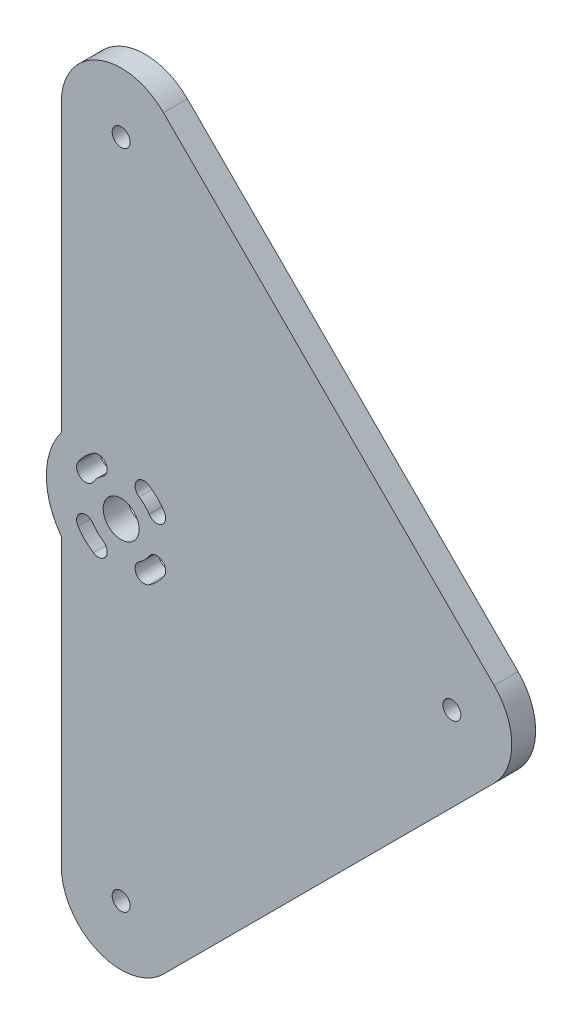
SolidWorks part; units mm, degrees
ref_plane "前视基准面" through (0, 0, 0) normal (0, 0, 1) x (1, 0, 0)
ref_plane "上视基准面" through (0, 0, 0) normal (0, 1, 0) x (1, 0, 0)
ref_plane "右视基准面" through (0, 0, 0) normal (1, 0, 0) x (0, 0, -1)
sketch "草图1" plane through (0, 0, 0) normal (0, 0, 1) x (1, 0, 0)
  line L0 (1790.7974, 1613.2668) -> (1790.7974, 1565.512)
  line L1 (1790.7974, 1550.512) -> (1790.7974, 1502.7572)
  line L2 (1807.8684, 1620.3379) -> (1863.1233, 1565.0831)
  line L3 (1863.1233, 1550.9409) -> (1807.8684, 1495.6861)
  circle A0 centre (1800.7974, 1558.012) radius 3
  circle A1 centre (1800.7974, 1613.2668) radius 1.5
  circle A2 centre (1856.0522, 1558.012) radius 1.5
  circle A3 centre (1800.7974, 1502.7572) radius 1.5
  arc A4 (1790.7974, 1502.7572) -> (1807.8684, 1495.6861) centre (1800.7974, 1502.7572) ccw
  arc A5 (1807.8684, 1620.3379) -> (1790.7974, 1613.2668) centre (1800.7974, 1613.2668) ccw
  arc A6 (1863.1233, 1550.9409) -> (1863.1233, 1565.0831) centre (1856.0522, 1558.012) ccw
  arc A7 (1790.7974, 1565.512) -> (1790.7974, 1550.512) centre (1800.7974, 1558.012) ccw
  arc A8 (1805.4433, 1550.8093) -> (1808.0001, 1553.3661) centre (1800.7974, 1558.012) ccw
  arc A9 (1808.0001, 1562.6579) -> (1805.4433, 1565.2147) centre (1800.7974, 1558.012) ccw
  arc A10 (1796.1515, 1565.2147) -> (1793.5947, 1562.6579) centre (1800.7974, 1558.012) ccw
  arc A11 (1793.5947, 1553.3661) -> (1796.1515, 1550.8093) centre (1800.7974, 1558.012) ccw
  arc A12 (1803.8171, 1553.3304) -> (1805.479, 1554.9923) centre (1800.7974, 1558.012) ccw
  arc A13 (1805.479, 1561.0318) -> (1803.8171, 1562.6937) centre (1800.7974, 1558.012) ccw
  arc A14 (1797.7776, 1562.6937) -> (1796.1157, 1561.0318) centre (1800.7974, 1558.012) ccw
  arc A15 (1796.1157, 1554.9923) -> (1797.7776, 1553.3304) centre (1800.7974, 1558.012) ccw
  arc A16 (1805.4433, 1565.2147) -> (1803.8171, 1562.6937) centre (1804.6302, 1563.9542) ccw
  arc A17 (1805.479, 1561.0318) -> (1808.0001, 1562.6579) centre (1806.7395, 1561.8448) ccw
  arc A18 (1797.7776, 1562.6937) -> (1796.1515, 1565.2147) centre (1796.9645, 1563.9542) ccw
  arc A19 (1793.5947, 1562.6579) -> (1796.1157, 1561.0318) centre (1794.8552, 1561.8448) ccw
  arc A20 (1796.1157, 1554.9923) -> (1793.5947, 1553.3661) centre (1794.8552, 1554.1792) ccw
  arc A21 (1796.1515, 1550.8093) -> (1797.7776, 1553.3304) centre (1796.9645, 1552.0698) ccw
  arc A22 (1803.8171, 1553.3304) -> (1805.4433, 1550.8093) centre (1804.6302, 1552.0698) ccw
  arc A23 (1808.0001, 1553.3661) -> (1805.479, 1554.9923) centre (1806.7395, 1554.1792) ccw
extrude "凸台-拉伸1" add sketch "草图1" along normal blind 4
